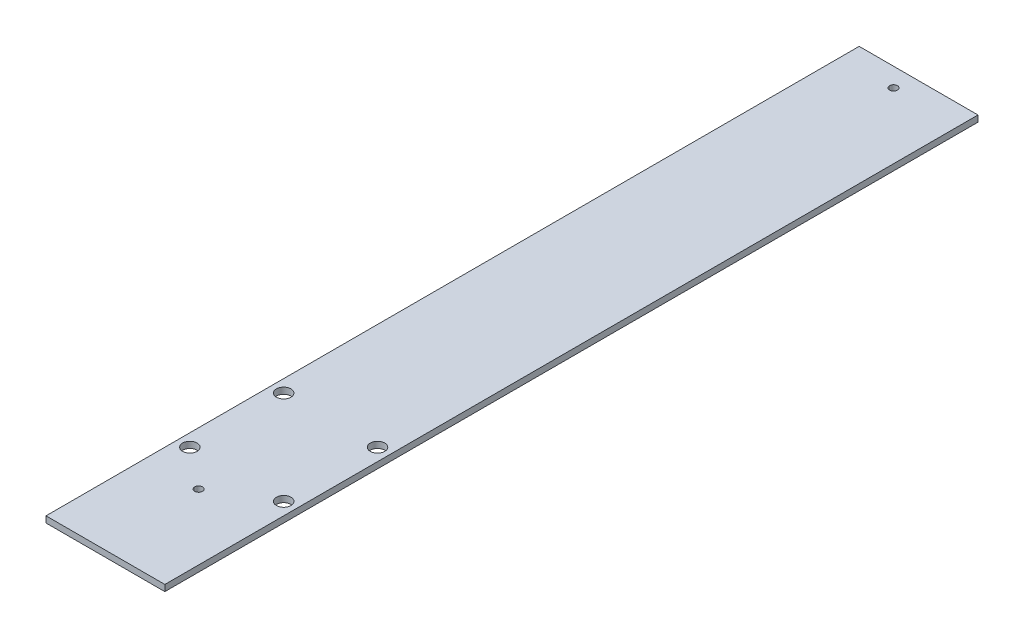
SolidWorks part; units mm, degrees
material "Alloy Steel"
ref_plane "Front" through (0, 0, 0) normal (0, 0, 1) x (1, 0, 0)
ref_plane "Top" through (0, 0, 0) normal (0, 1, 0) x (1, 0, 0)
ref_plane "Right" through (0, 0, 0) normal (1, 0, 0) x (0, 0, -1)
sketch "Sketch1" plane through (0, 0, 0) normal (0, 1, 0) x (1, 0, 0)
  line L1 (0, 0) -> (241.3, 0)
  line L2 (0, 0) -> (0, -1651)
  line L3 (0, -1651) -> (241.3, -1651)
  line L4 (241.3, 0) -> (241.3, -1651)
  dimension "D1" = 241.3
  dimension "D2" = 1651
extrude "Boss-Extrude1" add sketch "Sketch1" along normal blind 12.7
sketch "Sketch2" plane through (0, 12.7, 0) normal (0, 1, 0) x (1, 0, 0)
  line L0 (241.3, 0) -> (0, 0) construction
  line L1 (0, 0) -> (0, -1651) construction
  circle A0 centre (107.95, -38.1) radius 7.9375
  circle A1 centre (107.95, -1449.0573) radius 7.9375
  dimension "D1" = 15.875
  dimension "D2" = 15.875
  dimension "D3" = 1410.9573
  dimension "D4" = 38.1
  dimension "D5" = 107.95
extrude "Cut-Extrude1" cut sketch "Sketch2" against normal through all both and the other way through all
sketch "Sketch3" plane through (0, 0, 0) normal (0, -1, 0) x (1, 0, 0)
  circle A0 centre (215.9, 1193.8) radius 14.7295
  circle A1 centre (25.4, 1193.8) radius 14.7295
  circle A2 centre (25.4, 1384.3) radius 14.7295
  circle A3 centre (215.9, 1384.3) radius 14.7295
extrude "Cut-Extrude2" cut sketch "Sketch3" against normal through all
sketch "Sketch4" plane through (0, 0, 0) normal (0, -1, 0) x (1, 0, 0)
  line L0 (115.8875, 38.1) -> (100.0125, 38.1)
  circle A1 centre (107.95, 38.1) radius 7.9375 construction
  point P6 (107.95, 49.2724)
  point P7 (107.95, 38.1)
  point P8 (106.5331, 43.9632)
  point P9 (107.95, 46.0375)
  point P10 (109.4311, 45.8981)
  dimension "D1" = 15.875
split line "Split Line1"
sketch "Sketch5" plane through (0, 0, 0) normal (0, -1, 0) x (1, 0, 0)
  line L0 (115.8875, 1449.0573) -> (100.0125, 1449.0573)
  circle A0 centre (107.95, 1449.0573) radius 7.9375 construction
  dimension "D1" = 15.875
split line "Split Line2"
